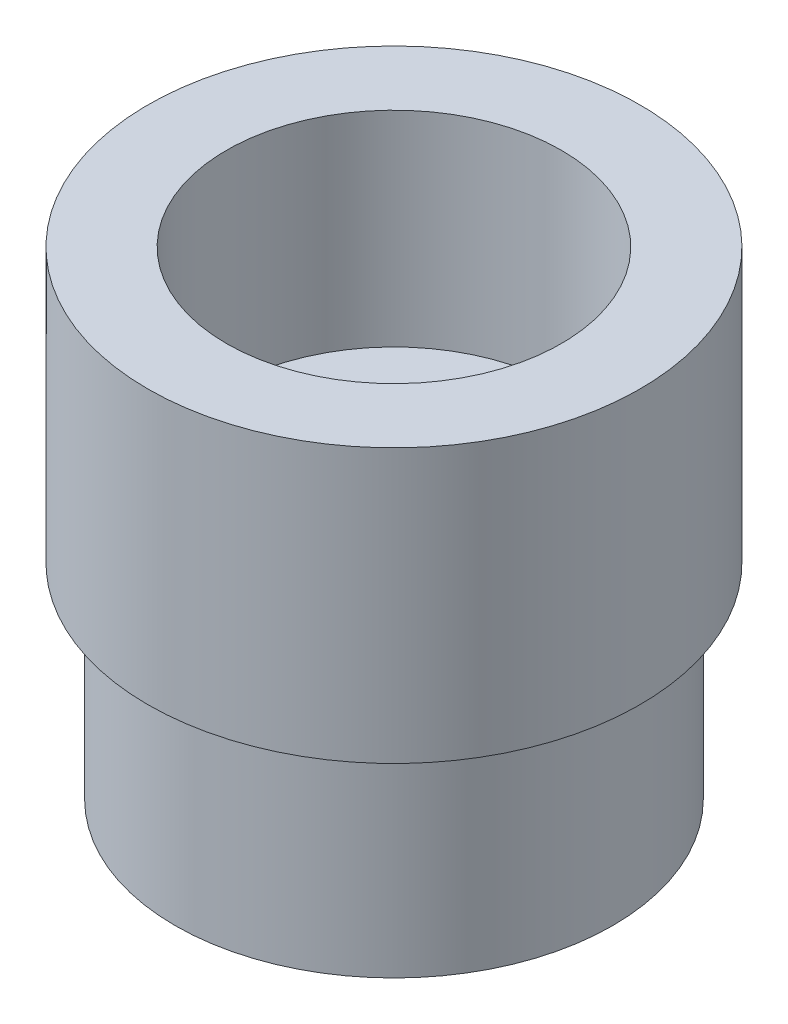
SolidWorks part; units mm, degrees
ref_plane "Front Plane" through (0, 0, 0) normal (0, 0, 1) x (1, 0, 0)
ref_plane "Top Plane" through (0, 0, 0) normal (0, 1, 0) x (1, 0, 0)
ref_plane "Right Plane" through (0, 0, 0) normal (1, 0, 0) x (0, 0, -1)
sketch "Sketch1" plane through (0, 0, 0) normal (0, 1, 0) x (1, 0, 0)
  circle A0 centre (0, 0) radius 4.572
  dimension "D1" = 9.144
extrude "Boss-Extrude1" add sketch "Sketch1" along normal blind 5.08
sketch "Sketch2" plane through (0, 5.08, 0) normal (0, 1, 0) x (1, 0, 0)
  circle A0 centre (0, 0) radius 3.1115
  dimension "D1" = 6.223
extrude "Cut-Extrude1" cut sketch "Sketch2" against normal blind 3.81
sketch "Sketch3" plane through (0, 0, 0) normal (0, -1, 0) x (-1, 0, 0)
  circle A0 centre (0, 0) radius 2.794
  dimension "D1" = 5.588
extrude "Extrude-Thin1" add sketch "Sketch3" along normal blind 3.81 thin
